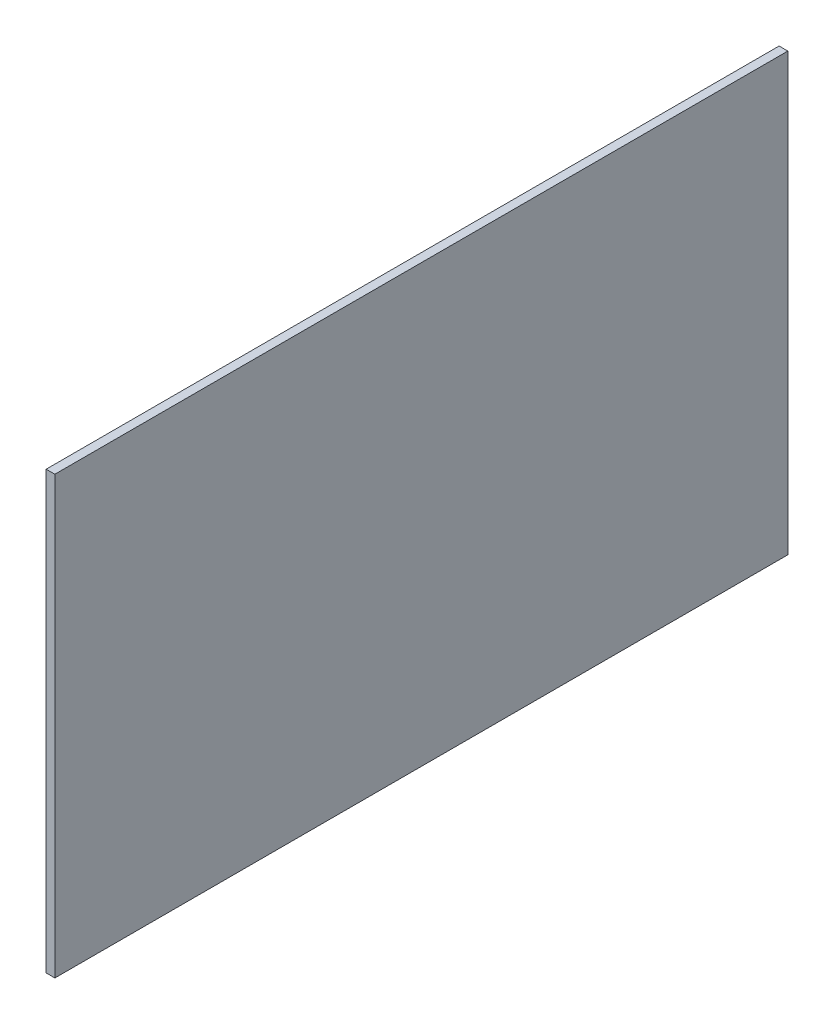
SolidWorks part; units mm, degrees
ref_plane "Front Plane" through (0, 0, 0) normal (0, 0, 1) x (1, 0, 0)
ref_plane "Top Plane" through (0, 0, 0) normal (0, 1, 0) x (1, 0, 0)
ref_plane "Right Plane" through (0, 0, 0) normal (1, 0, 0) x (0, 0, -1)
sketch "Sketch1" plane through (0, 0, 0) normal (1, 0, 0) x (0, 0, -1)
  line L1 (-12801.6, 8255) -> (12801.6, 8255)
  line L2 (-12801.6, 8255) -> (-12801.6, -6985)
  line L3 (-12801.6, -6985) -> (12801.6, -6985)
  line L4 (12801.6, 8255) -> (12801.6, -6985)
  line L5 (-12801.6, 8255) -> (12801.6, -6985) construction
  line L6 (-12801.6, -6985) -> (12801.6, 8255) construction
  point P0 (0, 635)
  point P5 (0, 0)
  point P6 (0, 0)
  dimension "D1" = 25603.2
  dimension "D2" = 15240
extrude "Boss-Extrude1" add sketch "Sketch1" along normal blind 304.8
sketch "Sketch2" plane through (304.8, 0, 0) normal (1, 0, 0) x (0, 0, -1)
  line L0 (-12801.6, 8255) -> (-12801.6, -6985) construction
  line L1 (-12801.6, 2567.6103) -> (12801.6, 2567.6103)
  line L2 (-12801.6, 2567.6103) -> (-12801.6, 818.0011)
  line L3 (-12801.6, 818.0011) -> (12801.6, 818.0011)
  line L4 (12801.6, 2567.6103) -> (12801.6, 818.0011)
  line L5 (12801.6, -6985) -> (12801.6, 8255) construction
  line L6 (-8673.0743, 7196.3108) -> (-1696.0681, 2567.6103)
  line L7 (-12801.6, 8255) -> (12801.6, 8255)
  line L8 (-12801.6, 8255) -> (-12801.6, 7196.3108)
  line L9 (-12801.6, 7196.3108) -> (12801.6, 7196.3108)
  line L10 (12801.6, 8255) -> (12801.6, 7196.3108)
  line L11 (-822.9927, 7196.3108) -> (725.6233, 7196.3108)
  line L12 (-822.9927, 7196.3108) -> (-822.9927, 2567.6103)
  line L13 (-822.9927, 2567.6103) -> (725.6233, 2567.6103)
  line L14 (725.6233, 7196.3108) -> (725.6233, 2567.6103)
  line L15 (-9761.8124, 7196.3108) -> (-8673.0743, 7196.3108)
  line L16 (-9761.8124, 7196.3108) -> (-9761.8124, 2567.6103)
  line L17 (-9761.8124, 2567.6103) -> (-8673.0743, 2567.6103)
  line L18 (-8673.0743, 7196.3108) -> (-8673.0743, 2567.6103)
  line L19 (8992.7154, 7196.3108) -> (7513.6028, 7196.3108)
  line L20 (8992.7154, 7196.3108) -> (8992.7154, 2567.6103)
  line L21 (8992.7154, 2567.6103) -> (7513.6028, 2567.6103)
  line L22 (7513.6028, 7196.3108) -> (7513.6028, 2567.6103)
  line L23 (-8673.0743, 7196.3108) -> (-7799.9989, 7196.3108)
  line L24 (-1696.0681, 2567.6103) -> (-822.9927, 2567.6103)
  line L25 (-7799.9989, 7196.3108) -> (-822.9927, 2567.6103)
  line L26 (725.6233, 2567.6103) -> (6127.751, 7196.3108)
  line L27 (725.6233, 2567.6103) -> (2111.4752, 2567.6103)
  line L28 (6127.751, 7196.3108) -> (7513.6028, 7196.3108)
  line L29 (2111.4752, 2567.6103) -> (7513.6028, 7196.3108)
  line L30 (-12801.6, 2567.6103) -> (-9761.8124, 7196.3108)
  line L31 (-12801.6, 2567.6103) -> (-14676.2941, 2567.6103)
  line L32 (-9761.8124, 7196.3108) -> (-11636.5065, 7196.3108)
  line L33 (-14676.2941, 2567.6103) -> (-11636.5065, 7196.3108)
  line L34 (8992.7154, 7196.3108) -> (12801.6, 2567.6103)
  line L35 (8992.7154, 7196.3108) -> (10545.0302, 7196.3108)
  line L36 (12801.6, 2567.6103) -> (14353.9148, 2567.6103)
  line L37 (10545.0302, 7196.3108) -> (14353.9148, 2567.6103)
  line L38 (12801.6, 8255) -> (-12801.6, 8255) construction
  line L39 (-12801.6, -3605.0175) -> (12801.6, -3605.0175)
  line L40 (-12801.6, -3605.0175) -> (-12801.6, -6985)
  line L41 (-12801.6, -6985) -> (12801.6, -6985)
  line L42 (12801.6, -3605.0175) -> (12801.6, -6985)
  line L43 (-12801.6, -6184.6202) -> (12801.6, -6184.6202)
  line L44 (-12801.6, -6184.6202) -> (-12801.6, -6985)
  line L45 (-12801.6, -6985) -> (12801.6, -6985)
  line L46 (12801.6, -6184.6202) -> (12801.6, -6985)
  point P3 (0, 0)
  point P29 (-12801.6, 8255)
